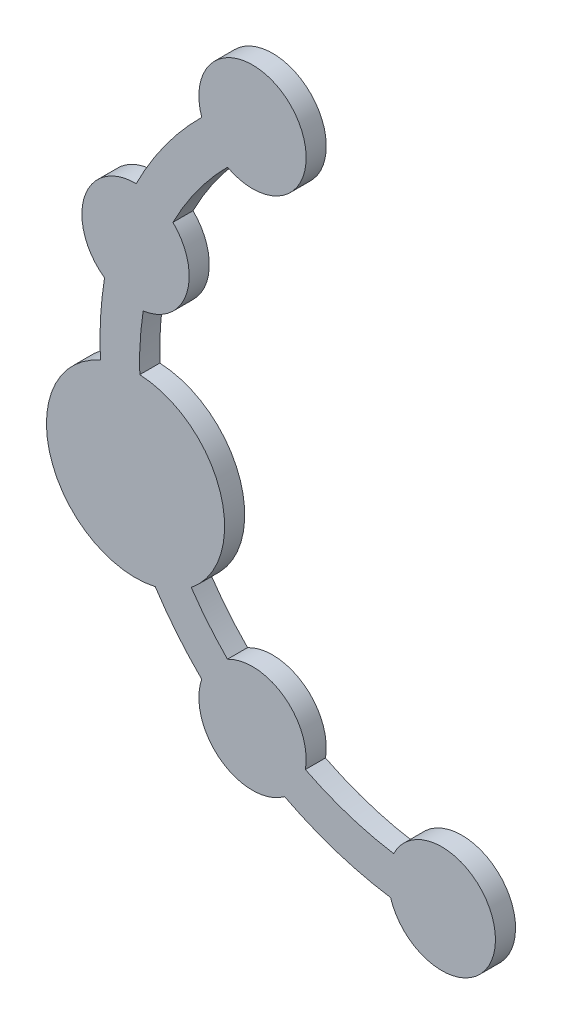
SolidWorks part; units mm, degrees
ref_plane "Front Plane" through (0, 0, 0) normal (0, 0, 1) x (1, 0, 0)
ref_plane "Top Plane" through (0, 0, 0) normal (0, 1, 0) x (1, 0, 0)
ref_plane "Right Plane" through (0, 0, 0) normal (1, 0, 0) x (0, 0, -1)
sketch "Sketch1" plane through (0, 0, 0) normal (0, 0, 1) x (1, 0, 0)
  line L0 (0, 0) -> (0, -32.53) construction
  line L1 (0, 0) -> (-19.1207, -26.3173) construction
  circle A0 centre (0, 0) radius 32.53 construction
  circle A1 centre (0, -32.53) radius 5.42
  circle A2 centre (-19.1207, -26.3173) radius 5.42
  circle A3 centre (-30.9379, -10.0523) radius 5.42
  circle A4 centre (-30.9379, 10.0523) radius 5.42
  circle A5 centre (-19.1207, 26.3173) radius 5.42
  dimension "D1" = 65.06
  dimension "D2" = 10.84
  dimension "D4" = 36
  dimension "D3" = 5
extrude "Boss-Extrude1" add sketch "Sketch1" along normal blind 2.03
sketch "Sketch2" plane through (0, 0, 2.03) normal (0, 0, 1) x (1, 0, 0)
  line L0 (0, 0) -> (0, -32.53) construction
  line L1 (-20.2962, 27.9354) -> (-17.9451, 24.6993)
  line L2 (0, -30.53) -> (0, -34.53)
  line L3 (-17.9451, 24.6993) -> (0, 0) construction
  arc A0 (0, -30.53) -> (-17.9451, 24.6993) centre (0, 0) cw
  arc A1 (0, -34.53) -> (-20.2962, 27.9354) centre (0, 0) cw
  circle A2 centre (0, 0) radius 32.53 construction
  point P8 (-19.1207, 26.3173)
  dimension "D1" = 2
extrude "Boss-Extrude2" add sketch "Sketch2" against normal blind 2.03
sketch "Sketch3" plane through (0, 0, 2.03) normal (0, 0, 1) x (1, 0, 0)
  circle A0 centre (-30.9379, -10.0523) radius 9
  dimension "D1" = 18
extrude "Boss-Extrude3" add sketch "Sketch3" against normal blind 2.03
